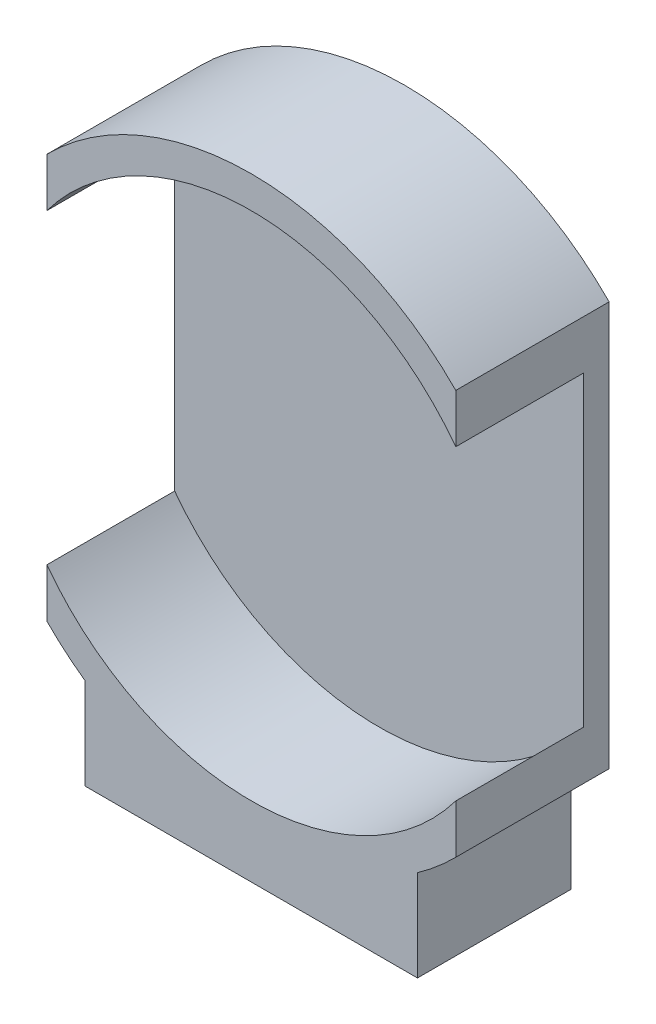
SolidWorks part; units mm, degrees
ref_plane "Front Plane" through (0, 0, 0) normal (0, 0, 1) x (1, 0, 0)
ref_plane "Top Plane" through (0, 0, 0) normal (0, 1, 0) x (1, 0, 0)
ref_plane "Right Plane" through (0, 0, 0) normal (1, 0, 0) x (0, 0, -1)
sketch "Sketch1" plane through (0, 0, 0) normal (0, 0, 1) x (1, 0, 0)
  circle A0 centre (0, 0) radius 11.25
  dimension "D1" = 22.5
extrude "Boss-Extrude1" add sketch "Sketch1" along normal blind 6
sketch "Sketch4" plane through (0, 0, 0) normal (0, 0, 1) x (1, 0, 0)
  line L0 (-18, 22.5) -> (18, 22.5)
  line L1 (-8, 12.5) -> (8, 12.5)
  line L2 (-8, 12.5) -> (-8, -12.5)
  line L3 (-8, -12.5) -> (8, -12.5)
  line L4 (8, 12.5) -> (8, -12.5)
  line L5 (-8, 12.5) -> (8, -12.5) construction
  line L6 (-8, -12.5) -> (8, 12.5) construction
  line L7 (18, 22.5) -> (18, -22.5)
  line L8 (-18, -22.5) -> (18, -22.5)
  line L9 (-18, 22.5) -> (-18, -22.5)
  point P0 (0, 0)
  dimension "D1" = 16
  dimension "D2" = 25
  dimension "D3" = 10
extrude "Cut-Extrude3" cut sketch "Sketch4" along normal through all
sketch "Sketch5" plane through (0, 0, 0) normal (0, 0, 1) x (1, 0, 0)
  line L0 (0, 0) -> (0, -12.75) construction
  line L1 (-6.5, 4.25) -> (6.5, 4.25)
  line L2 (-6.5, 4.25) -> (-6.5, -12.75)
  line L3 (-6.5, -12.75) -> (6.5, -12.75)
  line L4 (6.5, 4.25) -> (6.5, -12.75)
  line L5 (0, 11.25) -> (9.2727, 11.25) construction
  arc A0 (8, 7.9096) -> (-8, 7.9096) centre (0, 0) ccw construction
  dimension "D1" = 24
  dimension "D2" = 13
  dimension "D3" = 7
extrude "Boss-Extrude2" add sketch "Sketch5" along normal up to surface (6 mm away) up to face at (0, 0, 6)
sketch "Sketch2" plane through (0, 0, 6) normal (0, 0, 1) x (1, 0, 0)
  circle A0 centre (0, 0) radius 10
  dimension "D1" = 20
extrude "Cut-Extrude4" cut sketch "Sketch2" against normal offset from surface (5 mm away) 1 up to face at (0, -5.0737, 0)
sketch "Sketch6" plane through (0, -12.75, 0) normal (0, -1, 0) x (1, 0, 0)
  line L1 (-1.5, 0.3) -> (1.5, 0.3)
  line L2 (-1.5, 0.3) -> (-1.5, 0)
  line L3 (-1.5, 0) -> (1.5, 0)
  line L4 (1.5, 0.3) -> (1.5, 0)
  dimension "D1" = 3
  dimension "D2" = 0.3
extrude "Boss-Extrude3" add sketch "Sketch6" along normal blind 1.6
